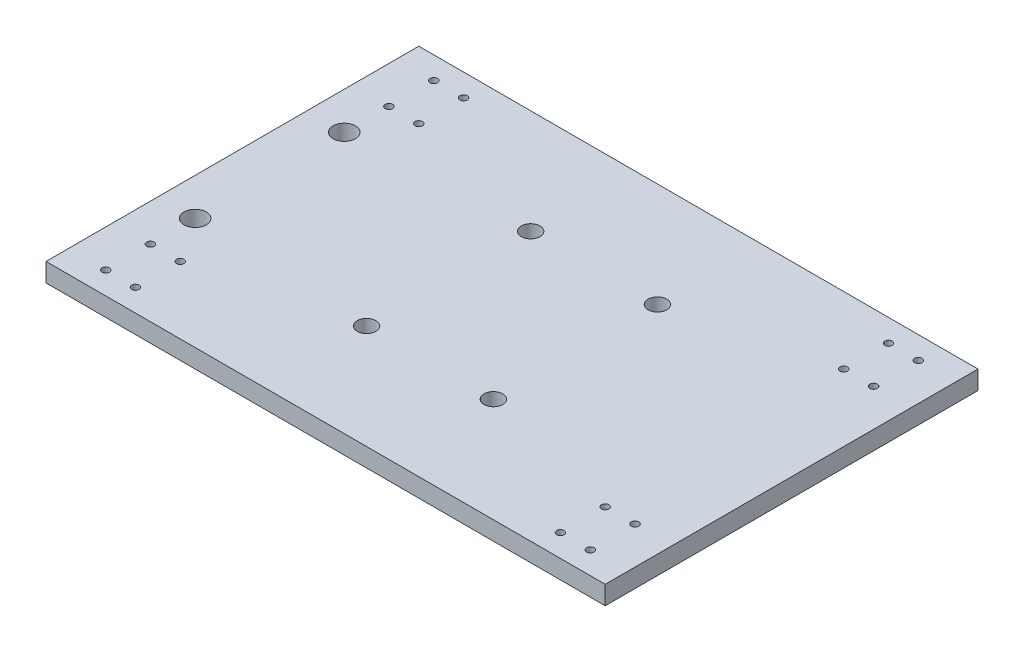
SolidWorks part; units mm, degrees
ref_plane "Front Plane" through (0, 0, 0) normal (0, 0, 1) x (1, 0, 0)
ref_plane "Top Plane" through (0, 0, 0) normal (0, 1, 0) x (1, 0, 0)
ref_plane "Right Plane" through (0, 0, 0) normal (1, 0, 0) x (0, 0, -1)
sketch "Sketch1" plane through (0, 0, 0) normal (0, 1, 0) x (1, 0, 0)
  line L1 (-75, 50) -> (75, 50)
  line L2 (-75, 50) -> (-75, -50)
  line L3 (-75, -50) -> (75, -50)
  line L4 (75, 50) -> (75, -50)
  line L5 (-75, 50) -> (75, -50) construction
  line L6 (-75, -50) -> (75, 50) construction
  point P0 (0, 0)
  dimension "D1" = 100
  dimension "D2" = 150
extrude "Boss-Extrude1" add sketch "Sketch1" along normal blind 5
sketch "Sketch2" plane through (0, 5, 0) normal (0, 1, 0) x (1, 0, 0)
  line L0 (0, 50) -> (0, -50) construction
  line L1 (75, 50) -> (-75, 50) construction
  line L2 (-75, -50) -> (75, -50) construction
  line L3 (-75, 0) -> (75, 0) construction
  line L4 (-75, 50) -> (-75, -50) construction
  line L5 (75, -50) -> (75, 50) construction
  circle A0 centre (17, 22) radius 2.5
  circle A1 centre (17, -22) radius 2.5
  circle A2 centre (-17, 22) radius 2.5
  circle A3 centre (-17, -22) radius 2.5
  circle A4 centre (65, 44) radius 1
  circle A5 centre (65, 32) radius 1
  circle A12 centre (57, 44) radius 1
  circle A13 centre (57, 32) radius 1
  circle A14 centre (65, -32) radius 1
  circle A15 centre (57, -32) radius 1
  circle A16 centre (65, -44) radius 1
  circle A17 centre (57, -44) radius 1
  circle A18 centre (-65, 32) radius 1
  circle A19 centre (-57, 32) radius 1
  circle A20 centre (-65, 44) radius 1
  circle A21 centre (-57, 44) radius 1
  circle A22 centre (-57, -44) radius 1
  circle A23 centre (-65, -44) radius 1
  circle A24 centre (-57, -32) radius 1
  circle A25 centre (-65, -32) radius 1
  dimension "D2" = 5
  dimension "D4" = 2
  dimension "D1" = 17
  dimension "D3" = 22
  dimension "D5" = 12
  dimension "D6" = 32
  dimension "D7" = 10
  dimension "D8" = 8
extrude "Cut-Extrude1" cut sketch "Sketch2" against normal through all
sketch "Sketch3" plane through (0, 5, 0) normal (0, 1, 0) x (1, 0, 0)
  line L0 (0, 0) -> (-75, 0) construction
  line L2 (-75, 50) -> (-75, -50) construction
  circle A2 centre (-65, 20) radius 3
  circle A3 centre (-65, -20) radius 3
  dimension "D1" = 6
  dimension "D2" = 20
  dimension "D3" = 10
extrude "Cut-Extrude2" cut sketch "Sketch3" against normal through all
